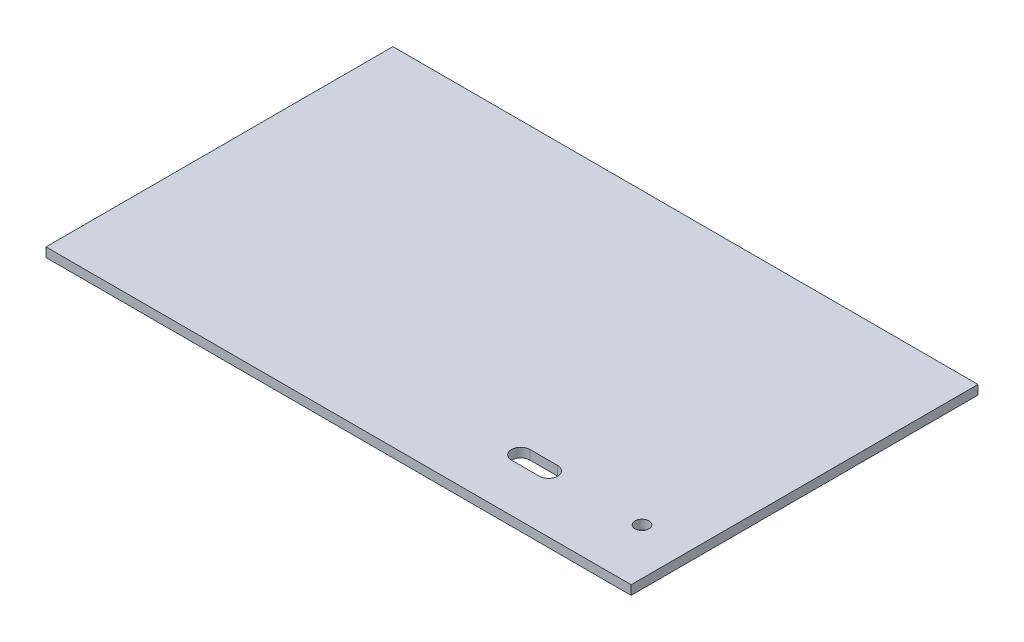
SolidWorks part; units mm, degrees
ref_plane "Front Plane" through (0, 0, 0) normal (0, 0, 1) x (1, 0, 0)
ref_plane "Top Plane" through (0, 0, 0) normal (0, 1, 0) x (1, 0, 0)
ref_plane "Right Plane" through (0, 0, 0) normal (1, 0, 0) x (0, 0, -1)
sketch "Sketch2" plane through (0, 0, 0) normal (0, 1, 0) x (1, 0, 0)
  line L1 (126.5, 75) -> (-126.5, 75)
  line L2 (126.5, 75) -> (126.5, -75)
  line L3 (126.5, -75) -> (-126.5, -75)
  line L4 (-126.5, 75) -> (-126.5, -75)
  line L5 (126.5, 75) -> (-126.5, -75) construction
  line L6 (126.5, -75) -> (-126.5, 75) construction
  point P0 (0, 0)
  dimension "D1" = 253
  dimension "D2" = 150
extrude "Boss-Extrude1" add sketch "Sketch2" along normal blind 4
sketch "Sketch3" plane through (0, 4, 0) normal (0, 1, 0) x (1, 0, 0)
  line L0 (66, -50.2278) -> (54, -50.2278) construction
  line L1 (66, -54.2278) -> (54, -54.2278)
  line L2 (66, -46.2278) -> (54, -46.2278)
  circle A0 centre (106.44, -50.2278) radius 3
  arc A2 (66, -54.2278) -> (66, -46.2278) centre (66, -50.2278) ccw
  arc A3 (54, -46.2278) -> (54, -54.2278) centre (54, -50.2278) ccw
  point P4 (60, -50.2278)
  dimension "D1" = 6
  dimension "D2" = 12
  dimension "D3" = 8
  dimension "D4" = 60
extrude "Cut-Extrude1" cut sketch "Sketch3" against normal through all
